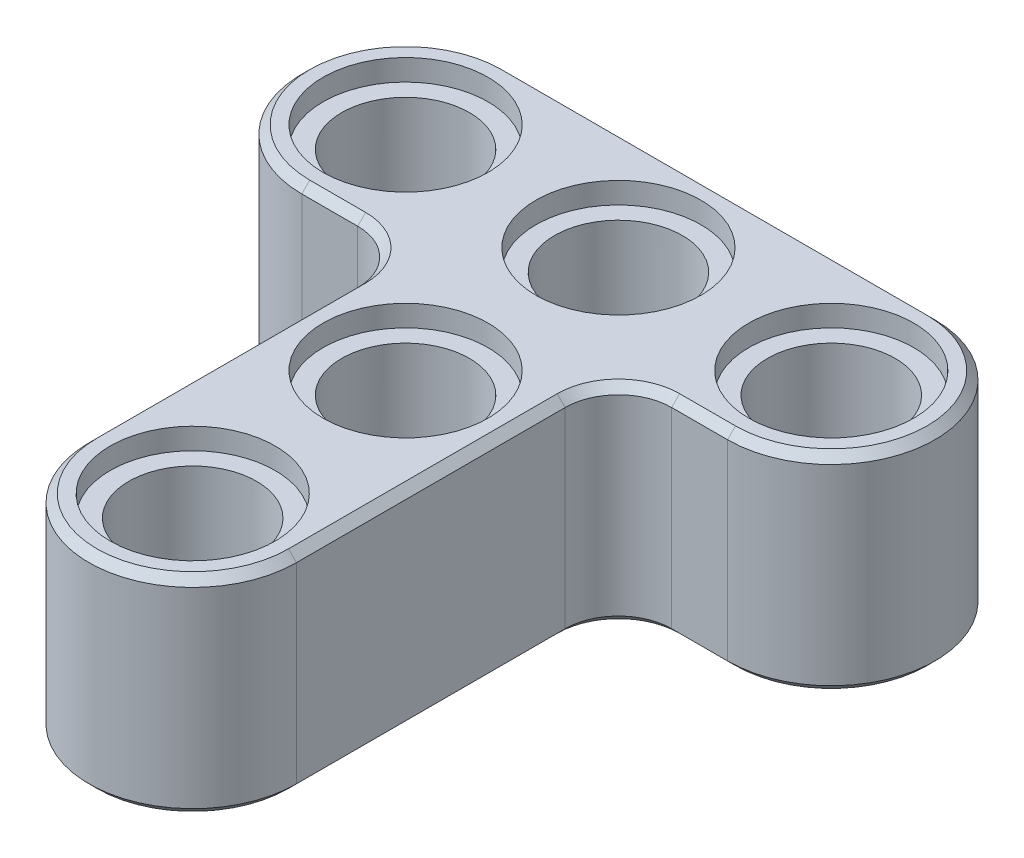
SolidWorks part; units mm, degrees
ref_plane "Front Plane" through (0, 0, 0) normal (0, 0, 1) x (1, 0, 0)
ref_plane "Top Plane" through (0, 0, 0) normal (0, 1, 0) x (1, 0, 0)
ref_plane "Right Plane" through (0, 0, 0) normal (1, 0, 0) x (0, 0, -1)
sketch "Sketch1" plane through (0, 0, 0) normal (0, 1, 0) x (1, 0, 0)
  line L0 (-8, 0) -> (8, 0) construction
  line L1 (0, 0) -> (0, -16) construction
  line L2 (-8, -3.9) -> (8, -3.9)
  line L3 (-3.9, 0) -> (-3.9, -16)
  line L4 (-8, 3.9) -> (8, 3.9)
  line L5 (3.9, 0) -> (3.9, -16)
  arc A0 (-8, -3.9) -> (-8, 3.9) centre (-8, 0) cw
  arc A1 (8, -3.9) -> (8, 3.9) centre (8, 0) ccw
  arc A2 (-3.9, 0) -> (3.9, 0) centre (0, 0) cw
  arc A3 (-3.9, -16) -> (3.9, -16) centre (0, -16) ccw
  point P4 (0, 0)
  dimension "D1" = 16
  dimension "D2" = 16
  dimension "D3" = 3.9
  dimension "D4" = 3.9
extrude "Boss-Extrude1" add sketch "Sketch1" along normal mid plane 7.8 contours L5 A3 L3 A2 | L2 A1 L4 A0
sketch "Sketch2" plane through (0, 3.9, 0) normal (0, 1, 0) x (1, 0, 0)
  circle A0 centre (0, 0) radius 2.4
  dimension "D1" = 4.8
extrude "Cut-Extrude1" cut sketch "Sketch2" against normal through all
sketch "Sketch3" plane through (0, 3.9, 0) normal (0, 1, 0) x (1, 0, 0)
  circle A0 centre (0, 0) radius 3.1
  dimension "D1" = 6.2
extrude "Cut-Extrude2" cut sketch "Sketch3" against normal blind 0.8
mirror "Mirror1" about plane through (0, 0, 0) normal (0, 1, 0) of "Cut-Extrude2"
pattern_linear "LPattern1" count 2 spacing 8 along (-1, 0, 0) count 2 spacing 8 along (1, 0, 0) of "Mirror1", "Cut-Extrude2", "Cut-Extrude1"
pattern_linear "LPattern2" count 3 spacing 8 along (0, 0, 1) of "Mirror1", "Cut-Extrude1", "Cut-Extrude2"
fillet "Fillet1" radius 2 2 edges at (-3.9, 0, 3.9) (3.9, 0, 3.9)
chamfer "Chamfer1" distance 0.3 angle 45 20 edges at (11.9, -3.9, 0) (0, -3.9, -3.9) (6.95, -3.9, 3.9) (-11.9, -3.9, 0) (4.4858, -3.9, 4.4858) (-6.95, -3.9, 3.9) (3.9, -3.9, 10.95) (-4.4858, -3.9, 4.4858) (0, -3.9, 19.9) (-3.9, -3.9, 10.95) (-11.9, 3.9, 0) (0, 3.9, -3.9) (-6.95, 3.9, 3.9) (11.9, 3.9, 0) (-4.4858, 3.9, 4.4858) (6.95, 3.9, 3.9) (-3.9, 3.9, 10.95) (4.4858, 3.9, 4.4858) (0, 3.9, 19.9) (3.9, 3.9, 10.95)
